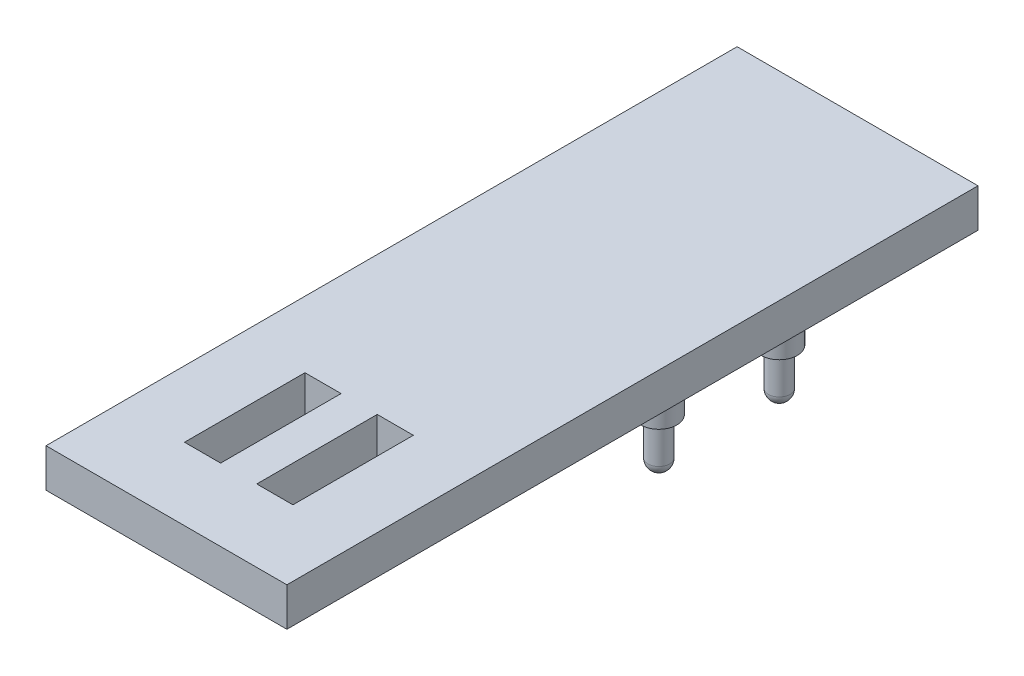
SolidWorks part; units mm, degrees
ref_plane "Front Plane" through (0, 0, 0) normal (0, 0, 1) x (1, 0, 0)
ref_plane "Top Plane" through (0, 0, 0) normal (0, 1, 0) x (1, 0, 0)
ref_plane "Right Plane" through (0, 0, 0) normal (1, 0, 0) x (0, 0, -1)
sketch "Sketch1" plane through (0, 0, 0) normal (0, 1, 0) x (1, 0, 0)
  line L0 (-5, -2.8868) -> (5, -2.8868) construction
  line L9 (0, 5.7735) -> (-5, -2.8868) construction
  line L10 (-5, -2.8868) -> (5, -2.8868) construction
  line L11 (5, -2.8868) -> (0, 5.7735) construction
  line L12 (-5, -5.8868) -> (-5, -37.5768)
  line L13 (5, -5.8868) -> (5, -37.5768)
  line L14 (-5, -37.5768) -> (5, -37.5768)
  line L15 (-5, -23.5768) -> (5, -23.5768) construction
  line L16 (-5, -34.5768) -> (5, -34.5768) construction
  line L17 (0.75, -26.5768) -> (2.25, -26.5768)
  line L18 (-2.25, -26.5768) -> (-0.75, -26.5768)
  line L19 (-2.25, -26.5768) -> (-2.25, -31.5768)
  line L20 (-2.25, -31.5768) -> (-0.75, -31.5768)
  line L21 (-0.75, -26.5768) -> (-0.75, -31.5768)
  line L22 (-1.5, -31.5768) -> (-1.5, -26.5768) construction
  line L23 (-2.25, -29.0768) -> (-0.75, -29.0768) construction
  line L24 (0.75, -26.5768) -> (0.75, -31.5768)
  line L25 (0.75, -31.5768) -> (2.25, -31.5768)
  line L26 (2.25, -26.5768) -> (2.25, -31.5768)
  line L27 (1.5, -31.5768) -> (1.5, -26.5768) construction
  line L28 (0.75, -29.0768) -> (2.25, -29.0768) construction
  line L29 (0, -37.5768) -> (0, -23.5768) construction
  line L30 (-5, -21.7318) -> (5, -21.7318) construction
  line L31 (-5, -5.8868) -> (5, -5.8868)
  line L32 (-5, -2.8868) -> (-5, -5.8868) construction
  line L33 (5, -2.8868) -> (5, -5.8868) construction
  circle A0 centre (0, 0) radius 5.7735 construction
  circle A1 centre (0, -34.5768) radius 1 construction
  circle A2 centre (0, -21.7318) radius 1 construction
  point P11 (-1.5, -29.0768)
  point P15 (1.5, -29.0768)
  dimension "D9" = 2
  dimension "D14" = 2
  dimension "D2" = 10
  dimension "D3" = 3
  dimension "D4" = 1.5
  dimension "D5" = 5
  dimension "D6" = 1.5
  dimension "D7" = 5
  dimension "D8" = 3
  dimension "D10" = 1.5
  dimension "D11" = 3
  dimension "D12" = 34.69
  dimension "D13" = 3
extrude "Boss-Extrude1" add sketch "Sketch1" along normal blind 1.6 contours L12 L14 L13 L0 A1 L18 L21 L20 L19 L17 L26 L25 L24 | L0 L11 L9
sketch "Sketch4" plane through (0, 0, 0) normal (0, -1, 0) x (1, 0, 0)
  line L0 (0, 14.1368) -> (0, 9.1368) construction
  line L1 (-5, 5.8868) -> (-5, 37.5768) construction
  line L2 (5, 5.8868) -> (5, 37.5768) construction
  line L4 (-5, 5.8868) -> (5, 5.8868) construction
  circle A0 centre (0, 9.1368) radius 1
  circle A1 centre (0, 14.1368) radius 1
  dimension "D2" = 2
  dimension "D3" = 2
  dimension "D1" = 5
  dimension "D4" = 3.25
extrude "Boss-Extrude2" add sketch "Sketch4" along normal blind 0.5
sketch "Sketch5" plane through (0, -0.5, 0) normal (0, -1, 0) x (1, 0, 0)
  circle A0 centre (0, 9.1368) radius 0.75
  circle A1 centre (0, 14.1368) radius 0.75
  dimension "D1" = 1.5
  dimension "D2" = 1.5
extrude "Boss-Extrude3" add sketch "Sketch5" along normal blind 4.5
sketch "Sketch6" plane through (0, -5, 0) normal (0, -1, 0) x (1, 0, 0)
  circle A0 centre (0, 9.1368) radius 0.45
  circle A1 centre (0, 14.1368) radius 0.45
  dimension "D1" = 0.9
  dimension "D2" = 0.9
extrude "Boss-Extrude4" add sketch "Sketch6" along normal blind 2
fillet "Fillet1" radius 0.45 2 edges at (0, -7, 13.6868) (0, -7, 8.6868)
sketch "Sketch7" plane through (0, 0, 0) normal (0, -1, 0) x (1, 0, 0)
  line L0 (-5, 37.5768) -> (5, 37.5768)
  line L1 (-5, 37.5768) -> (-5, 34.5768)
  line L2 (5, 37.5768) -> (5, 34.5768)
  line L3 (-5, 34.5768) -> (5, 34.5768)
  dimension "D1" = 3
extrude "Cut-Extrude1" cut sketch "Sketch7" against normal blind 10
